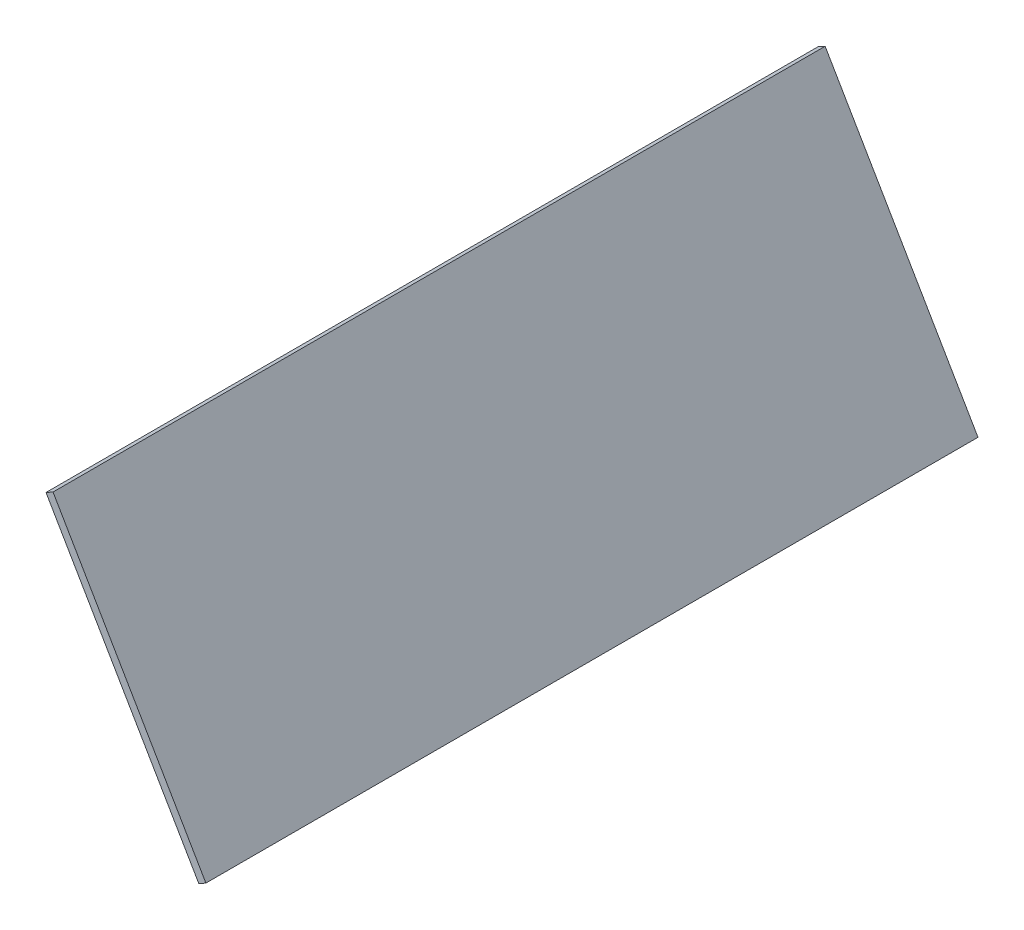
SolidWorks part; units mm, degrees
ref_plane "Front Plane" through (0, 0, 0) normal (0, 0, 1) x (1, 0, 0)
ref_plane "Top Plane" through (0, 0, 0) normal (0, 1, 0) x (1, 0, 0)
ref_plane "Right Plane" through (0, 0, 0) normal (1, 0, 0) x (0, 0, -1)
sketch "Sloping electronics bulkhead profile" plane through (0, 0, 0) normal (0, 0, 1) x (1, 0, 0)
  line L0 (54, 103) -> (55.8, 104)
  line L1 (55.8, 104) -> (95, 36.75)
  line L2 (95, 36.75) -> (93.2, 35.7)
  line L3 (93.2, 35.7) -> (54, 103)
extrude "Sloping electronics bulkhead" add sketch "Sloping electronics bulkhead profile" along normal blind 198
